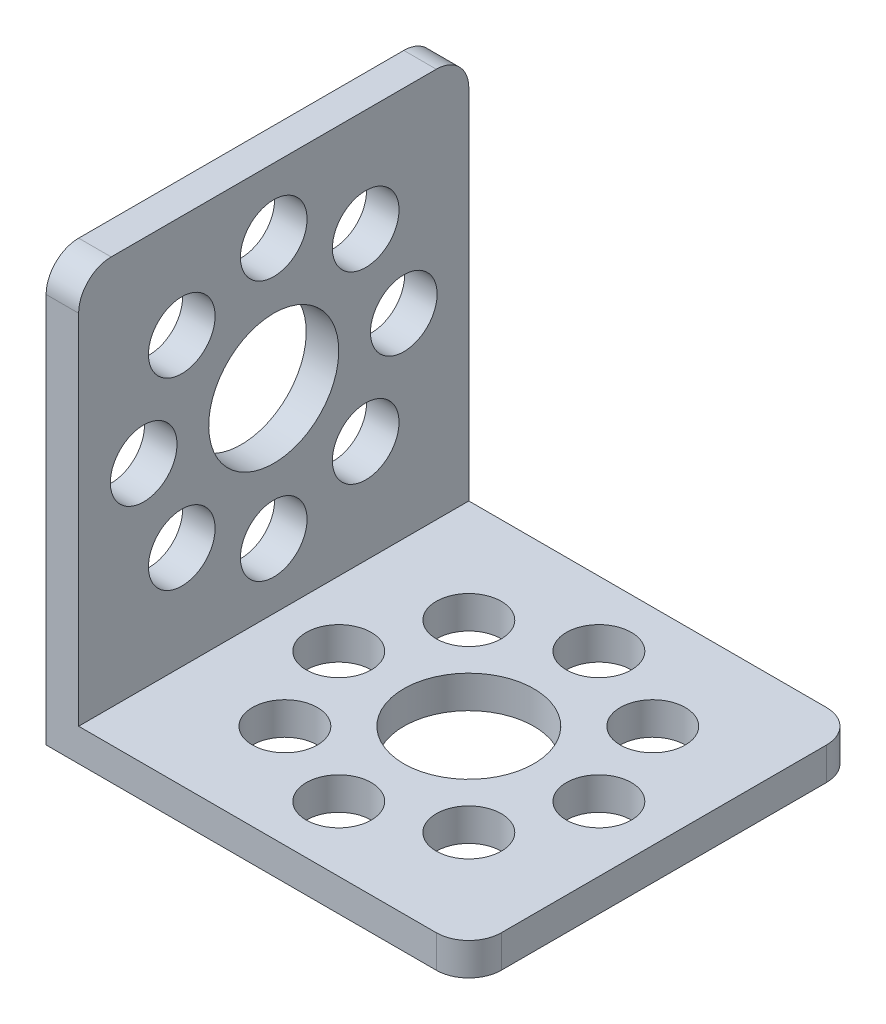
SolidWorks part; units mm, degrees
ref_plane "Front Plane" through (0, 0, 0) normal (0, 0, 1) x (1, 0, 0)
ref_plane "Top Plane" through (0, 0, 0) normal (0, 1, 0) x (1, 0, 0)
ref_plane "Right Plane" through (0, 0, 0) normal (1, 0, 0) x (0, 0, -1)
sketch "Sketch1" plane through (0, 0, 0) normal (0, 0, 1) x (1, 0, 0)
  line L0 (0, 0) -> (0, 26)
  line L1 (0, 26) -> (2, 26)
  line L2 (2, 26) -> (2, 2)
  line L3 (2, 2) -> (26, 2)
  line L4 (26, 2) -> (26, 0)
  line L5 (26, 0) -> (0, 0)
  dimension "D1" = 26
  dimension "D2" = 26
  dimension "D3" = 2
  dimension "D4" = 2
extrude "Boss-Extrude1" add sketch "Sketch1" along normal blind 24
sketch "Sketch2" plane through (2, 0, 0) normal (1, 0, 0) x (0, 0, -1)
  line L0 (-24, 26) -> (0, 26) construction
  line L2 (0, 2) -> (0, 26) construction
  circle A0 centre (-12, 22) radius 2.05
  circle A1 centre (-12, 14) radius 4
  circle A2 centre (-12, 14) radius 8 construction
  circle A3 centre (-6.3431, 19.6569) radius 2.05
  circle A4 centre (-4, 14) radius 2.05
  circle A5 centre (-6.3431, 8.3431) radius 2.05
  circle A6 centre (-12, 6) radius 2.05
  circle A7 centre (-17.6569, 8.3431) radius 2.05
  circle A8 centre (-20, 14) radius 2.05
  circle A9 centre (-17.6569, 19.6569) radius 2.05
  point P4 (-19.0313, 17.8159)
  point P5 (-12, 26)
  point P8 (0, 0)
  point P29 (-12, 14)
  dimension "D1" = 4.1
  dimension "D2" = 8
  dimension "D3" = 16
  dimension "D5" = 12
  dimension "D6" = 12
  dimension "D7" = 8
extrude "Cut-Extrude1" cut sketch "Sketch2" against normal through all
sketch "Sketch3" plane through (0, 2, 0) normal (0, 1, 0) x (1, 0, 0)
  line L2 (26, -24) -> (26, 0) construction
  line L4 (26, 0) -> (2, 0) construction
  circle A0 centre (14, -12) radius 4
  circle A1 centre (14, -12) radius 8 construction
  circle A2 centre (22, -12) radius 2
  circle A3 centre (19.6569, -17.6569) radius 2
  circle A4 centre (14, -20) radius 2
  circle A5 centre (8.3431, -17.6569) radius 2
  circle A6 centre (6, -12) radius 2
  circle A7 centre (8.3431, -6.3431) radius 2
  circle A8 centre (14, -4) radius 2
  circle A9 centre (19.6569, -6.3431) radius 2
  point P10 (14, -12)
  point P11 (14, -12)
  point P25 (14, -12)
  dimension "D1" = 8
  dimension "D4" = 16
  dimension "D5" = 4
  dimension "D2" = 12
  dimension "D3" = 12
  dimension "D6" = 8
extrude "Cut-Extrude2" cut sketch "Sketch3" against normal through all
fillet "Fillet1" radius 2 4 edges at (1, 26, 24) (1, 26, 0) (26, 1, 0) (26, 1, 24)
